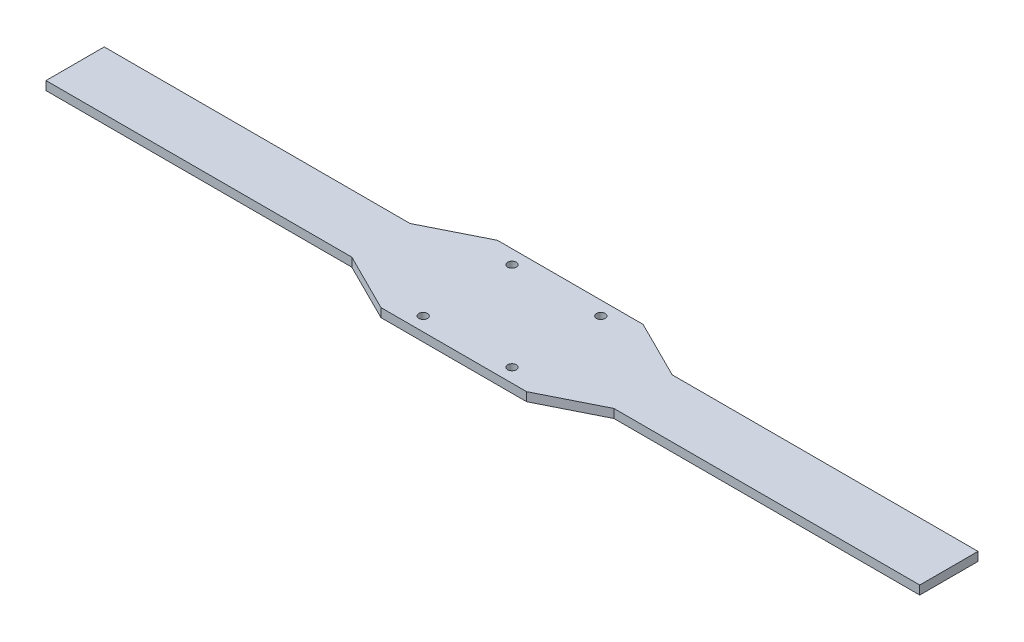
SolidWorks part; units mm, degrees
ref_plane "Front Plane" through (0, 0, 0) normal (0, 0, 1) x (1, 0, 0)
ref_plane "Top Plane" through (0, 0, 0) normal (0, 1, 0) x (1, 0, 0)
ref_plane "Right Plane" through (0, 0, 0) normal (1, 0, 0) x (0, 0, -1)
sketch "Sketch1" plane through (0, 0, 0) normal (0, 1, 0) x (1, 0, 0)
  line L0 (-150, 0) -> (150, 0) construction
  line L1 (15.25, 15.25) -> (-15.25, 15.25) construction
  line L2 (15.25, 15.25) -> (15.25, -15.25) construction
  line L3 (15.25, -15.25) -> (-15.25, -15.25) construction
  line L4 (-15.25, 15.25) -> (-15.25, -15.25) construction
  line L5 (15.25, 15.25) -> (-15.25, -15.25) construction
  line L6 (15.25, -15.25) -> (-15.25, 15.25) construction
  line L7 (150, 20) -> (-150, 20)
  line L8 (150, 20) -> (150, -20)
  line L9 (150, -20) -> (-150, -20)
  line L10 (-150, 20) -> (-150, -20)
  line L11 (150, 20) -> (-150, -20) construction
  line L12 (150, -20) -> (-150, 20) construction
  circle A0 centre (-15.25, 15.25) radius 1.5
  circle A1 centre (15.25, 15.25) radius 1.5
  circle A2 centre (15.25, -15.25) radius 1.5
  circle A3 centre (-15.25, -15.25) radius 1.5
  point P0 (0, 0)
  point P10 (0, 0)
  dimension "D2" = 3
  dimension "D1" = 30.5
  dimension "D3" = 300
  dimension "D4" = 40
extrude "Boss-Extrude1" add sketch "Sketch1" along normal mid plane 3
sketch "Sketch2" plane through (0, -1.5, 0) normal (0, -1, 0) x (1, 0, 0)
  line L0 (-150, 20) -> (-150, 10)
  line L1 (-150, -20) -> (-150, 20) construction
  line L2 (-150, 10) -> (-45, 10)
  line L3 (-45, 10) -> (-25, 20)
  line L4 (-150, 20) -> (150, 20) construction
  line L5 (-150, 20) -> (-25, 20)
  line L6 (0, 20) -> (0, -20) construction
  line L7 (150, -20) -> (-150, -20) construction
  line L8 (-150, 0) -> (150, 0) construction
  line L9 (150, 20) -> (150, -20) construction
  line L10 (150, 20) -> (25, 20)
  line L11 (45, 10) -> (25, 20)
  line L12 (150, 10) -> (45, 10)
  line L13 (150, 20) -> (150, 10)
  line L14 (150, -20) -> (150, -10)
  line L15 (150, -10) -> (45, -10)
  line L16 (45, -10) -> (25, -20)
  line L17 (150, -20) -> (25, -20)
  line L18 (-150, -20) -> (-25, -20)
  line L19 (-45, -10) -> (-25, -20)
  line L20 (-150, -10) -> (-45, -10)
  line L21 (-150, -20) -> (-150, -10)
  dimension "D1" = 105
  dimension "D2" = 20
  dimension "D3" = 10
extrude "Cut-Extrude1" cut sketch "Sketch2" against normal through all
